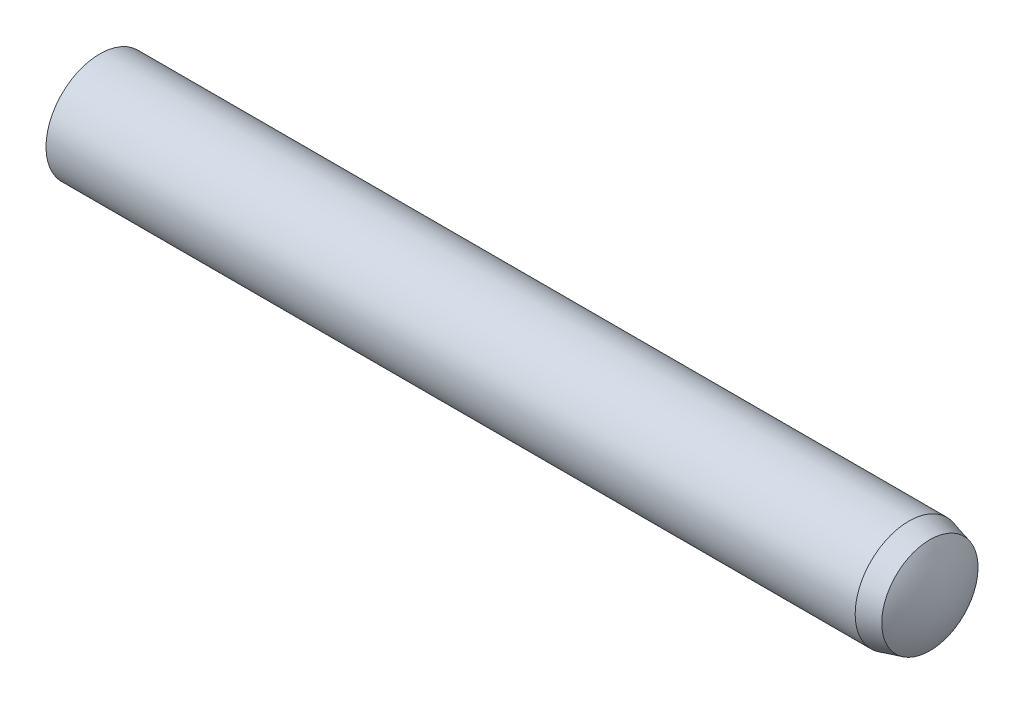
SolidWorks part; units mm, degrees
material "AISI 1015 Steel, Cold Drawn (SS)"
ref_plane "Front Plane" through (0, 0, 0) normal (0, 0, 1) x (1, 0, 0)
ref_plane "Top Plane" through (0, 0, 0) normal (0, 1, 0) x (1, 0, 0)
ref_plane "Right Plane" through (0, 0, 0) normal (1, 0, 0) x (0, 0, -1)
sketch "Sketch1" plane through (0, 0, 0) normal (0, 0, 1) x (1, 0, 0)
  line L0 (-12, 0) -> (12, 0) construction
  line L1 (12, 1.5) -> (12, -1.5) construction
  line L2 (-12, 1.5) -> (-12, -1.5) construction
  line L3 (11.025, 1.5) -> (11.025, -1.5) construction
  line L4 (-11.55, 1.5) -> (-11.55, -1.5) construction
  line L5 (-12, 0) -> (-11.55, 0) construction
  line L6 (12, 0) -> (11.025, 0) construction
  line L7 (11.61, 1.5) -> (11.61, -1.5) construction
  dimension "D1" = 0.975
  dimension "Dia" = 3
  dimension "D2" = 0.45
  dimension "Length" = 24
  dimension "D3" = 0.585
sketch "Sketch2" plane through (0, 0, 0) normal (1, 0, 0) x (0, 0, -1)
  circle A0 centre (0, 0) radius 1.5
extrude "Extrude1" add sketch "Sketch2" against normal up to vertex (12 mm away) and the other way up to vertex (12 mm away) up to point (-12, 0, 0) other way up to point (12, 0, 0)
sketch "Sketch5" plane through (0, 0, 0) normal (0, 0, 1) x (1, 0, 0)
  line L0 (11.025, 1.5) -> (11.025, 2)
  line L1 (11.025, 2) -> (12.5, 2)
  line L2 (12.5, 2) -> (12.5, 0)
  line L3 (12, 0) -> (12.5, 0)
  line L5 (-11.55, 1.5) -> (-11.55, 2)
  line L6 (-11.55, 2) -> (-12.5, 2)
  line L7 (-12.5, 2) -> (-12.5, 0)
  line L8 (11.025, 1.5) -> (11.61, 1.3432)
  line L10 (-12, 0) -> (-12.5, 0)
  line L11 (-12, 1.5) -> (-12, -1.5) construction
  line L13 (11.025, 1.5) -> (11.025, -1.5) construction
  line L15 (-12, 0) -> (12, 0) construction
  line L16 (11.61, 1.5) -> (11.61, -1.5) construction
  line L17 (12, 1.5) -> (12, -1.5) construction
  arc A0 (11.61, 1.3432) -> (12, 0) centre (9.4918, 0) cw
  arc A1 (-11.55, 1.5) -> (-12, 0) centre (-9.275, 0) ccw
  dimension "D1" = 15
  dimension "D2" = 0.5
revolve "Cut-Revolve1" cut sketch "Sketch5" angle 360 about L0
equation "\"D1@Sketch1\" = \"Dia@Sketch1\"*.325"
equation "\"D2@Sketch1\" = \"Dia@Sketch1\"*.15"
equation "\"D3@Sketch1\" = \"D1@Sketch1\"*.6"
